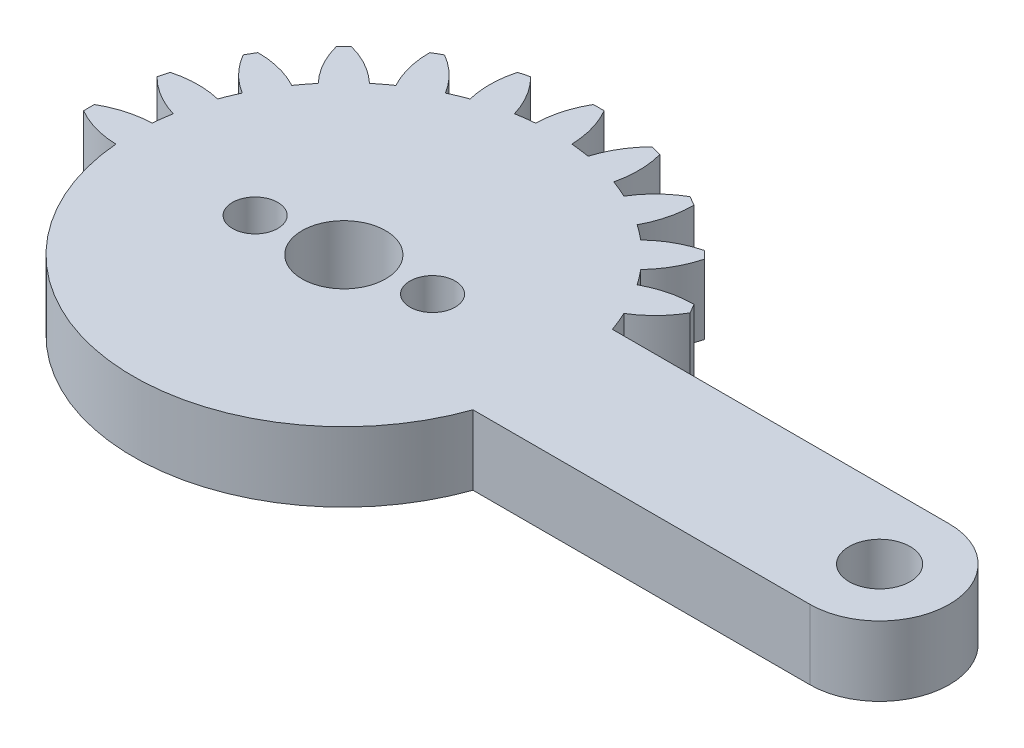
SolidWorks part; units mm, degrees
ref_plane "Front Plane" through (0, 0, 0) normal (0, 0, 1) x (1, 0, 0)
ref_plane "Top Plane" through (0, 0, 0) normal (0, 1, 0) x (1, 0, 0)
ref_plane "Right Plane" through (0, 0, 0) normal (1, 0, 0) x (0, 0, -1)
sketch "Sketch1" plane through (0, 0, 0) normal (0, 1, 0) x (1, 0, 0)
  line L0 (30.75, 4) -> (11.4091, 4)
  line L1 (30.75, -4) -> (11.4091, -4)
  arc A0 (11.4091, 4) -> (11.4091, -4) centre (0, 0) ccw
  arc A1 (30.75, -4) -> (30.75, 4) centre (30.75, 0) ccw
  circle A2 centre (30.75, 0) radius 1.75
  circle A3 centre (0, 0) radius 1.75
  dimension "D1" = 24.18
  dimension "D2" = 8
  dimension "D3" = 3.5
  dimension "D4" = 3.5
  dimension "D5" = 30.75
  dimension "D6" = 19.3409
extrude "Boss-Extrude1" add sketch "Sketch1" along normal blind 4
sketch "Sketch3" plane through (0, 4, 0) normal (0, 1, 0) x (1, 0, 0)
  line L0 (-41.9688, 0) -> (41.9688, 0) construction
  line L1 (0, -14.63) -> (0, 14.63) construction
  arc A0 (12.8221, 7.0449) -> (12.5121, 7.5818) centre (0, 0) ccw
  arc A1 (-14.6267, 0.31) -> (-12.0452, 1.04) centre (-11.9126, -4.3584) cw
  arc A2 (11.4091, 4) -> (11.4091, -4) centre (0, 0) ccw construction
  arc A3 (-14.6267, -0.31) -> (-12.0452, -1.04) centre (-11.9126, 4.3584) ccw
  arc A4 (-14.0481, 4.0851) -> (-11.3656, 4.1221) centre (-12.6347, -1.1267) cw
  arc A5 (-14.2086, 3.4862) -> (-11.9039, 2.113) centre (-10.3787, 7.2931) ccw
  arc A6 (-12.5121, 7.5818) -> (-9.9114, 6.9233) centre (-12.4958, 2.1819) cw
  arc A7 (-12.8221, 7.0449) -> (-10.9514, 5.1219) centre (-8.1374, 9.7308) ccw
  arc A8 (-10.1234, 10.5619) -> (-7.7818, 9.2526) centre (-11.5053, 5.3417) cw
  arc A9 (-10.5619, 10.1234) -> (-9.2526, 7.7818) centre (-5.3417, 11.5053) ccw
  arc A10 (-7.0449, 12.8221) -> (-5.1219, 10.9514) centre (-9.7308, 8.1374) cw
  arc A11 (-7.5818, 12.5121) -> (-6.9233, 9.9114) centre (-2.1819, 12.4958) ccw
  arc A12 (-3.4862, 14.2086) -> (-2.113, 11.9039) centre (-7.2931, 10.3787) cw
  arc A13 (-4.0851, 14.0481) -> (-4.1221, 11.3656) centre (1.1267, 12.6347) ccw
  arc A14 (0.31, 14.6267) -> (1.04, 12.0452) centre (-4.3584, 11.9126) cw
  arc A15 (-0.31, 14.6267) -> (-1.04, 12.0452) centre (4.3584, 11.9126) ccw
  arc A16 (4.0851, 14.0481) -> (4.1221, 11.3656) centre (-1.1267, 12.6347) cw
  arc A17 (3.4862, 14.2086) -> (2.113, 11.9039) centre (7.2931, 10.3787) ccw
  arc A18 (7.5818, 12.5121) -> (6.9233, 9.9114) centre (2.1819, 12.4958) cw
  arc A19 (7.0449, 12.8221) -> (5.1219, 10.9514) centre (9.7308, 8.1374) ccw
  arc A20 (10.5619, 10.1234) -> (9.2526, 7.7818) centre (5.3417, 11.5053) cw
  arc A21 (10.1234, 10.5619) -> (7.7818, 9.2526) centre (11.5053, 5.3417) ccw
  arc A22 (12.8221, 7.0449) -> (10.9514, 5.1219) centre (8.1374, 9.7308) cw
  arc A23 (12.5121, 7.5818) -> (9.9114, 6.9233) centre (12.4958, 2.1819) ccw
  arc A24 (10.9514, 5.1219) -> (9.9114, 6.9233) centre (0, 0) ccw
  arc A25 (10.5619, 10.1234) -> (10.1234, 10.5619) centre (0, 0) ccw
  arc A26 (9.2526, 7.7818) -> (7.7818, 9.2526) centre (0, 0) ccw
  arc A27 (6.9233, 9.9114) -> (5.1219, 10.9514) centre (0, 0) ccw
  arc A28 (7.5818, 12.5121) -> (7.0449, 12.8221) centre (0, 0) ccw
  arc A29 (4.0851, 14.0481) -> (3.4862, 14.2086) centre (0, 0) ccw
  arc A30 (4.1221, 11.3656) -> (2.113, 11.9039) centre (0, 0) ccw
  arc A31 (1.04, 12.0452) -> (-1.04, 12.0452) centre (0, 0) ccw
  arc A32 (0.31, 14.6267) -> (-0.31, 14.6267) centre (0, 0) ccw
  arc A33 (-3.4862, 14.2086) -> (-4.0851, 14.0481) centre (0, 0) ccw
  arc A34 (-2.113, 11.9039) -> (-4.1221, 11.3656) centre (0, 0) ccw
  arc A35 (-5.1219, 10.9514) -> (-6.9233, 9.9114) centre (0, 0) ccw
  arc A36 (-7.0449, 12.8221) -> (-7.5818, 12.5121) centre (0, 0) ccw
  arc A37 (-10.1234, 10.5619) -> (-10.5619, 10.1234) centre (0, 0) ccw
  arc A38 (-7.7818, 9.2526) -> (-9.2526, 7.7818) centre (0, 0) ccw
  arc A39 (-9.9114, 6.9233) -> (-10.9514, 5.1219) centre (0, 0) ccw
  arc A40 (-12.5121, 7.5818) -> (-12.8221, 7.0449) centre (0, 0) ccw
  arc A41 (-14.0481, 4.0851) -> (-14.2086, 3.4862) centre (0, 0) ccw
  arc A42 (-11.3656, 4.1221) -> (-11.9039, 2.113) centre (0, 0) ccw
  arc A43 (-12.0452, 1.04) -> (-12.0452, -1.04) centre (0, 0) ccw
  arc A44 (-14.6267, 0.31) -> (-14.6267, -0.31) centre (0, 0) ccw
  arc A50 (-14.2086, -3.4862) -> (-11.9039, -2.113) centre (-10.3787, -7.2931) cw [skipped]
  arc A51 (-14.0481, -4.0851) -> (-11.3656, -4.1221) centre (-12.6347, 1.1267) ccw [skipped]
  arc A52 (-12.8221, -7.0449) -> (-10.9514, -5.1219) centre (-8.1374, -9.7308) cw [skipped]
  arc A53 (-12.5121, -7.5818) -> (-9.9114, -6.9233) centre (-12.4958, -2.1819) ccw [skipped]
  arc A54 (-10.5619, -10.1234) -> (-9.2526, -7.7818) centre (-5.3417, -11.5053) cw [skipped]
  arc A55 (-10.1234, -10.5619) -> (-7.7818, -9.2526) centre (-11.5053, -5.3417) ccw [skipped]
  arc A56 (-7.5818, -12.5121) -> (-6.9233, -9.9114) centre (-2.1819, -12.4958) cw [skipped]
  arc A57 (-7.0449, -12.8221) -> (-5.1219, -10.9514) centre (-9.7308, -8.1374) ccw [skipped]
  arc A58 (-4.0851, -14.0481) -> (-4.1221, -11.3656) centre (1.1267, -12.6347) cw [skipped]
  arc A59 (-3.4862, -14.2086) -> (-2.113, -11.9039) centre (-7.2931, -10.3787) ccw [skipped]
  arc A60 (-0.31, -14.6267) -> (-1.04, -12.0452) centre (4.3584, -11.9126) cw [skipped]
  arc A61 (0.31, -14.6267) -> (1.04, -12.0452) centre (-4.3584, -11.9126) ccw [skipped]
  arc A62 (3.4862, -14.2086) -> (2.113, -11.9039) centre (7.2931, -10.3787) cw [skipped]
  arc A63 (4.0851, -14.0481) -> (4.1221, -11.3656) centre (-1.1267, -12.6347) ccw [skipped]
  arc A64 (7.5818, -12.5121) -> (6.9233, -9.9114) centre (2.1819, -12.4958) ccw [skipped]
  arc A65 (7.0449, -12.8221) -> (5.1219, -10.9514) centre (9.7308, -8.1374) cw [skipped]
  arc A66 (10.1234, -10.5619) -> (7.7818, -9.2526) centre (11.5053, -5.3417) cw [skipped]
  arc A67 (10.5619, -10.1234) -> (9.2526, -7.7818) centre (5.3417, -11.5053) ccw [skipped]
  arc A68 (12.5121, -7.5818) -> (9.9114, -6.9233) centre (12.4958, -2.1819) cw [skipped]
  arc A69 (12.8221, -7.0449) -> (10.9514, -5.1219) centre (8.1374, -9.7308) ccw [skipped]
  arc A70 (14.0481, -4.0851) -> (11.3656, -4.1221) centre (12.6347, 1.1267) cw [skipped]
  arc A71 (14.2086, -3.4862) -> (11.9039, -2.113) centre (10.3787, -7.2931) ccw [skipped]
  arc A72 (14.6267, -0.31) -> (12.0452, -1.04) centre (11.9126, 4.3584) cw [skipped]
  arc A73 (14.6267, 0.31) -> (12.0452, 1.04) centre (11.9126, -4.3584) ccw [skipped]
  arc A74 (14.2086, 3.4862) -> (11.9039, 2.113) centre (10.3787, 7.2931) cw [skipped]
  arc A75 (14.0481, 4.0851) -> (11.3656, 4.1221) centre (12.6347, -1.1267) ccw [skipped]
  point P6 (0, 0)
  point P9 (0, 0)
  dimension "D1" = 29.26
  dimension "D2" = 5.4
  dimension "D5" = 5.4
  dimension "D3" = 0.31
  dimension "D4" = 0.31
  dimension "D6" = 1.04
  dimension "D7" = 2.08
  dimension "D8" = 24
extrude "Boss-Extrude3" add sketch "Sketch3" against normal blind 4
sketch "Sketch4" plane through (0, 4, 0) normal (0, 1, 0) x (1, 0, 0)
  line L0 (-38.1232, 0) -> (38.1232, 0) construction
  line L1 (0, -21.327) -> (0, 21.327) construction
  line L2 (-33.1472, -4.3639) -> (33.1472, 4.3639) construction
  circle A1 centre (4.5, 0.5924) radius 1.3
  circle A2 centre (-4.5, -0.5924) radius 1.3
  circle A3 centre (0, 0) radius 2.4
  point P5 (0, 0)
  point P7 (0, 0)
  point P12 (0, 0)
  dimension "D2" = 2.6
  dimension "D3" = 2.6
  dimension "D4" = 4.8
  dimension "D5" = 4.5
  dimension "D6" = 4.5
  dimension "D1" = 7.5
extrude "Cut-Extrude1" cut sketch "Sketch4" against normal blind 4
